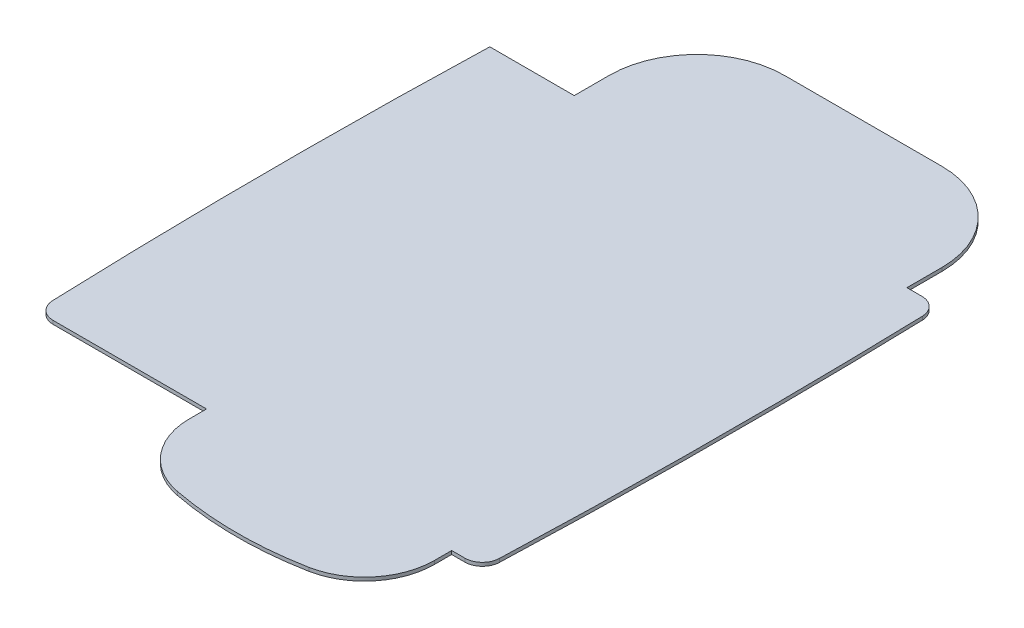
SolidWorks part; units mm, degrees
ref_plane "正面" through (0, 0, 0) normal (0, 0, 1) x (1, 0, 0)
ref_plane "平面" through (0, 0, 0) normal (0, 1, 0) x (1, 0, 0)
ref_plane "右側面" through (0, 0, 0) normal (1, 0, 0) x (0, 0, -1)
sketch "ｽｹｯﾁ1" plane through (0, 0, 0) normal (0, 1, 0) x (1, 0, 0)
  line L1 (-65, 92.5) -> (65, 92.5)
  line L2 (-65, 92.5) -> (-65, -92.5) construction
  line L3 (-65, -92.5) -> (65, -92.5)
  line L4 (65, 92.5) -> (65, -92.5) construction
  ellipse E0 centre (0, 0) end of major axis (0, -350) minor radius 65
  point P11 (-65, 0)
  dimension "D1" = 130
  dimension "D2" = 700
  dimension "D3" = 185
extrude "ﾎﾞｽ - 押し出し1" add sketch "ｽｹｯﾁ1" along normal mid plane 1 contours L3 E0 L1
sketch "ｽｹｯﾁ3" plane through (0, 0.5, 0) normal (0, 1, 0) x (1, 0, 0)
  line L0 (-62.6889, 92.5) -> (62.6889, 92.5) construction
  line L1 (-65, 92.5) -> (-40, 92.5)
  line L2 (-65, 92.5) -> (-65, 57.5)
  line L3 (-65, 57.5) -> (-40, 57.5)
  line L4 (-40, 92.5) -> (-40, 57.5)
  ellipse E0 centre (0, 0) end of major axis (0, -350) minor radius 65 (-62.6889, 92.5) -> (-62.6889, -92.5) ccw construction
  dimension "D1" = 35
  dimension "D2" = 25
extrude "ｶｯﾄ - 押し出し1" cut sketch "ｽｹｯﾁ3" against normal through all
sketch "ｽｹｯﾁ4" plane through (0, 0.5, 0) normal (0, 1, 0) x (1, 0, 0)
  line L0 (-40, 92.5) -> (62.6889, 92.5) construction
  line L1 (55, 92.5) -> (65, 92.5)
  line L2 (55, 92.5) -> (55, 57.5)
  line L3 (55, 57.5) -> (65, 57.5)
  line L4 (65, 92.5) -> (65, 57.5)
  line L5 (-64.1168, 57.5) -> (-40, 57.5) construction
  ellipse E0 centre (0, 0) end of major axis (0, -350) minor radius 65 (62.6889, -92.5) -> (62.6889, 92.5) ccw construction
  dimension "D1" = 10
extrude "ｶｯﾄ - 押し出し2" cut sketch "ｽｹｯﾁ4" against normal through all
sketch "ｽｹｯﾁ5" plane through (0, 0.5, 0) normal (0, 1, 0) x (1, 0, 0)
  line L0 (-62.6889, -92.5) -> (62.6889, -92.5) construction
  line L1 (-65, -72.5) -> (-15, -72.5)
  line L2 (-65, -72.5) -> (-65, -92.5)
  line L3 (-65, -92.5) -> (-15, -92.5)
  line L4 (-15, -72.5) -> (-15, -92.5)
  ellipse E0 centre (0, 0) end of major axis (0, -350) minor radius 65 (-64.1168, 57.5) -> (-62.6889, -92.5) ccw construction
  dimension "D1" = 20
  dimension "D2" = 50
extrude "ｶｯﾄ - 押し出し3" cut sketch "ｽｹｯﾁ5" against normal through all
sketch "ｽｹｯﾁ6" plane through (0, 0.5, 0) normal (0, 1, 0) x (1, 0, 0)
  line L0 (-15, -92.5) -> (62.6889, -92.5) construction
  line L1 (55, -72.5) -> (65, -72.5)
  line L2 (55, -72.5) -> (55, -92.5)
  line L3 (55, -92.5) -> (65, -92.5)
  line L4 (65, -72.5) -> (65, -92.5)
  line L7 (-15, -72.5) -> (-63.5902, -72.5) construction
  line L8 (55, 92.5) -> (55, 57.5) construction
  ellipse E0 centre (0, 0) end of major axis (0, -350) minor radius 65 (62.6889, -92.5) -> (64.1168, 57.5) ccw construction
extrude "ｶｯﾄ - 押し出し4" cut sketch "ｽｹｯﾁ6" against normal through all
sketch "ｽｹｯﾁ7" plane through (0, 0, 0) normal (0, 1, 0) x (1, 0, 0)
  line L0 (-15, -92.5) -> (55, -92.5) construction
  line L1 (-15, -92.5) -> (55, -92.5)
  arc A0 (-15, -92.5) -> (55, -92.5) centre (20, 1.175) ccw
  dimension "D1" = 100
extrude "ﾎﾞｽ - 押し出し2" add sketch "ｽｹｯﾁ7" along normal mid plane 1
sketch "ｽｹｯﾁ8" plane through (0, 0.5, 0) normal (0, 1, 0) x (1, 0, 0)
  line L0 (-40, 92.5) -> (55, 92.5) construction
  line L1 (-40, 57.5) -> (-40, 92.5) construction
  line L2 (55, 92.5) -> (55, 57.5) construction
  line L3 (55, 92.5) -> (55, 57.5)
  line L4 (-40, 92.5) -> (55, 92.5)
  line L5 (-40, 57.5) -> (-40, 92.5)
  circle A0 centre (-15, 67.5) radius 25
  circle A1 centre (30, 67.5) radius 25
  line M6 (55, 92.5) -> (-40, 92.5)
  line M7 (-40, 92.5) -> (-40, 57.5)
  dimension "D1" = 45
extrude "ｶｯﾄ - 押し出し5" cut sketch "ｽｹｯﾁ8" against normal through all contours A0 L4 M7 | A1 L3 M6
fillet "ﾌｨﾚｯﾄ1" radius 5 3 edges at (-63.5902, 0, 72.5) (63.5902, 0, 72.5) (64.1168, 0, -57.5)
fillet "ﾌｨﾚｯﾄ2" radius 20 2 edges at (-15, 0, 92.5) (55, 0, 92.5)
